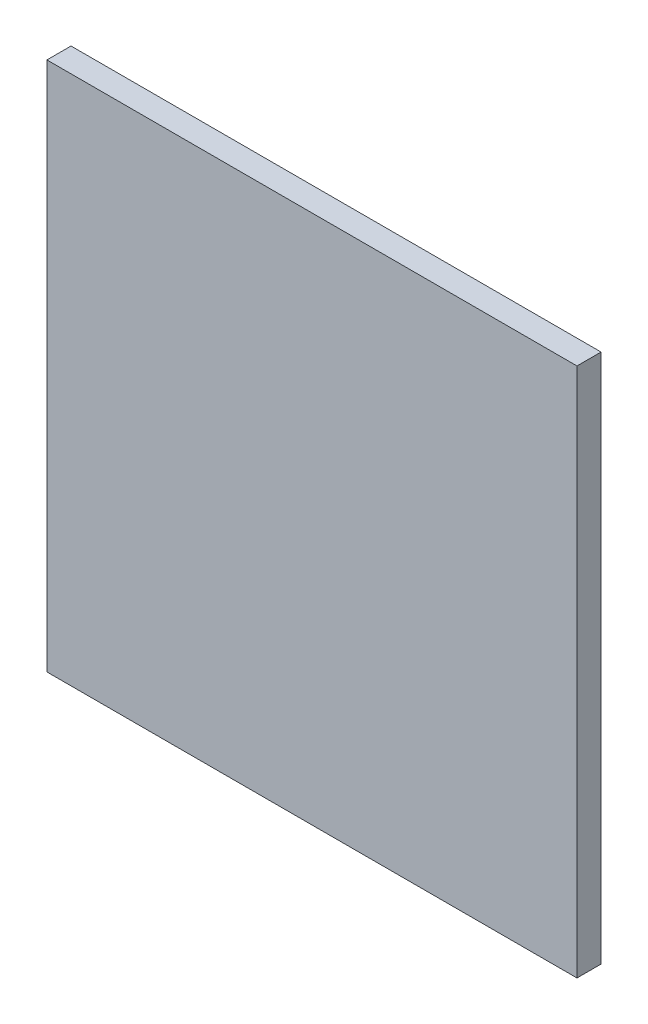
SolidWorks part; units mm, degrees
material "Сталь 3 ГОСТ 535-88"
ref_plane "Спереди" through (0, 0, 0) normal (0, 0, 1) x (1, 0, 0)
ref_plane "Сверху" through (0, 0, 0) normal (0, 1, 0) x (1, 0, 0)
ref_plane "Справа" through (0, 0, 0) normal (1, 0, 0) x (0, 0, -1)
sketch "Эскиз1" plane through (0, 0, 0) normal (0, 0, 1) x (1, 0, 0)
  line L1 (-55, -55) -> (55, -55)
  line L2 (-55, -55) -> (-55, 55)
  line L3 (-55, 55) -> (55, 55)
  line L4 (55, -55) -> (55, 55)
  line L5 (0, 55) -> (0, -55) construction
  line L6 (-55, 0) -> (55, 0) construction
  point P0 (0, 0)
  dimension "D1" = 110
  dimension "D2" = 110
extrude "Бобышка-Вытянуть1" add sketch "Эскиз1" along normal mid plane 5
